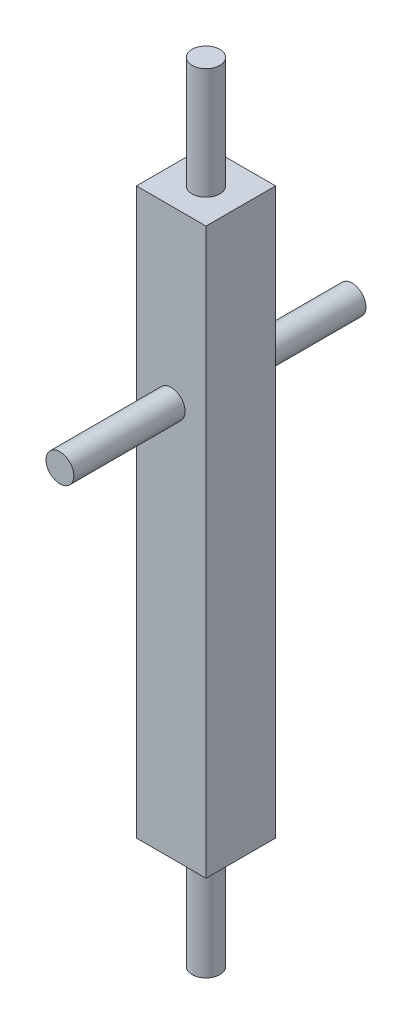
SolidWorks part; units mm, degrees
ref_plane "Front Plane" through (0, 0, 0) normal (0, 0, 1) x (1, 0, 0)
ref_plane "Top Plane" through (0, 0, 0) normal (0, 1, 0) x (1, 0, 0)
ref_plane "Right Plane" through (0, 0, 0) normal (1, 0, 0) x (0, 0, -1)
sketch "Sketch3" plane through (0, 0, 0) normal (0, 1, 0) x (1, 0, 0)
  line L0 (0, 86.7063) -> (0, -87.1032) construction
  line L1 (-136.9048, 0) -> (130.9524, 0) construction
  line L7 (-12.5, 12.5) -> (12.5, 12.5)
  line L8 (-12.5, 12.5) -> (-12.5, -12.5)
  line L13 (-12.5, -12.5) -> (12.5, -12.5)
  line L14 (12.5, 12.5) -> (12.5, -12.5)
  line L15 (-12.5, 12.5) -> (12.5, -12.5) construction
  line L16 (-12.5, -12.5) -> (12.5, 12.5) construction
  line L17 (-11, 11) -> (11, 11)
  line L18 (-11, 11) -> (-11, -11)
  line L19 (-11, -11) -> (11, -11)
  line L20 (11, 11) -> (11, -11)
  line L21 (-11, 11) -> (11, -11) construction
  line L22 (-11, -11) -> (11, 11) construction
  point P5 (0, 0)
  point P10 (0, 0)
  dimension "D1" = 25
  dimension "D2" = 25
  dimension "D3" = 22
extrude "Boss-Extrude1" add sketch "Sketch3" along normal blind 200
sketch "Sketch4" plane through (0, 0, 12.5) normal (0, 0, 1) x (1, 0, 0)
  line L0 (-12.5, 200) -> (12.5, 200) construction
  line L2 (12.5, 200) -> (12.5, 0) construction
  circle A0 centre (0, 140) radius 5
  dimension "D1" = 10
  dimension "D2" = 60
  dimension "D3" = 12.5
extrude "Cut-Extrude1" cut sketch "Sketch4" against normal blind 25
sketch "Sketch5" plane through (0, 0, 0) normal (0, 0, 1) x (1, 0, 0)
  circle A0 centre (0, 140) radius 5
extrude "Boss-Extrude2" add sketch "Sketch5" along normal blind 52.5 and the other way blind 52.5
sketch "Sketch6" plane through (0, 200, 0) normal (0, 1, 0) x (1, 0, 0)
  line L1 (-12.5, 12.5) -> (12.5, 12.5)
  line L2 (-12.5, 12.5) -> (-12.5, -12.5)
  line L3 (-12.5, -12.5) -> (12.5, -12.5)
  line L4 (12.5, 12.5) -> (12.5, -12.5)
  line L5 (-12.5, 12.5) -> (12.5, -12.5) construction
  line L6 (-12.5, -12.5) -> (12.5, 12.5) construction
  point P0 (0, 0)
extrude "Boss-Extrude3" add sketch "Sketch6" along normal blind 1.5
sketch "Sketch7" plane through (0, 0, 0) normal (0, -1, 0) x (1, 0, 0)
  line L1 (-12.5, 12.5) -> (12.5, 12.5)
  line L2 (-12.5, 12.5) -> (-12.5, -12.5)
  line L3 (-12.5, -12.5) -> (12.5, -12.5)
  line L4 (12.5, 12.5) -> (12.5, -12.5)
  line L5 (-12.5, 12.5) -> (12.5, -12.5) construction
  line L6 (-12.5, -12.5) -> (12.5, 12.5) construction
  point P0 (0, 0)
extrude "Boss-Extrude4" add sketch "Sketch7" along normal blind 1.5
sketch "Sketch8" plane through (0, -1.5, 0) normal (0, -1, 0) x (1, 0, 0)
  circle A0 centre (0, 0) radius 5
extrude "Boss-Extrude5" add sketch "Sketch8" along normal blind 40
sketch "Sketch9" plane through (0, 201.5, 0) normal (0, 1, 0) x (1, 0, 0)
  circle A0 centre (0, 0) radius 5
extrude "Boss-Extrude6" add sketch "Sketch9" along normal blind 40
